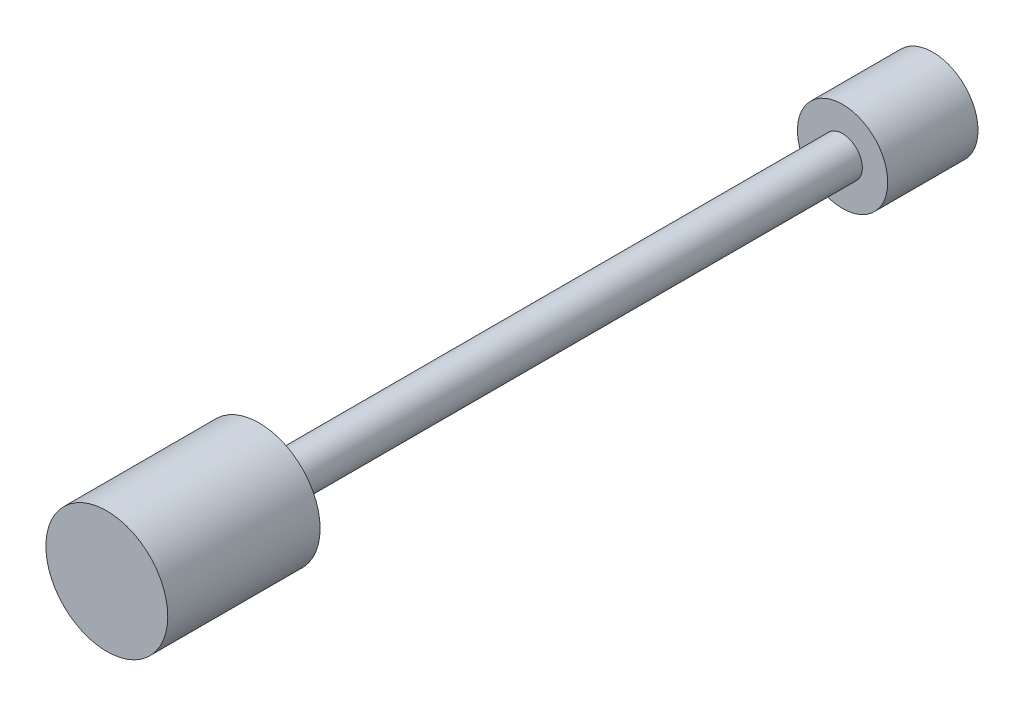
SolidWorks part; units mm, degrees
ref_plane "Front Plane" through (0, 0, 0) normal (0, 0, 1) x (1, 0, 0)
ref_plane "Top Plane" through (0, 0, 0) normal (0, 1, 0) x (1, 0, 0)
ref_plane "Right Plane" through (0, 0, 0) normal (1, 0, 0) x (0, 0, -1)
sketch "Sketch1" plane through (0, 0, 0) normal (0, 0, 1) x (1, 0, 0)
  circle A0 centre (0, 0) radius 4
  dimension "D1" = 8
extrude "Boss-Extrude1" add sketch "Sketch1" along normal blind 8
sketch "Sketch2" plane through (0, 0, 8) normal (0, 0, 1) x (1, 0, 0)
  circle A0 centre (0, 0) radius 1.75
  dimension "D1" = 3.5
extrude "Boss-Extrude2" add sketch "Sketch2" along normal blind 51.7
sketch "Sketch3" plane through (0, 0, 59.7) normal (0, 0, 1) x (1, 0, 0)
  circle A0 centre (0, 0) radius 5.4
  dimension "D1" = 10.8
extrude "Boss-Extrude3" add sketch "Sketch3" along normal blind 13.5
